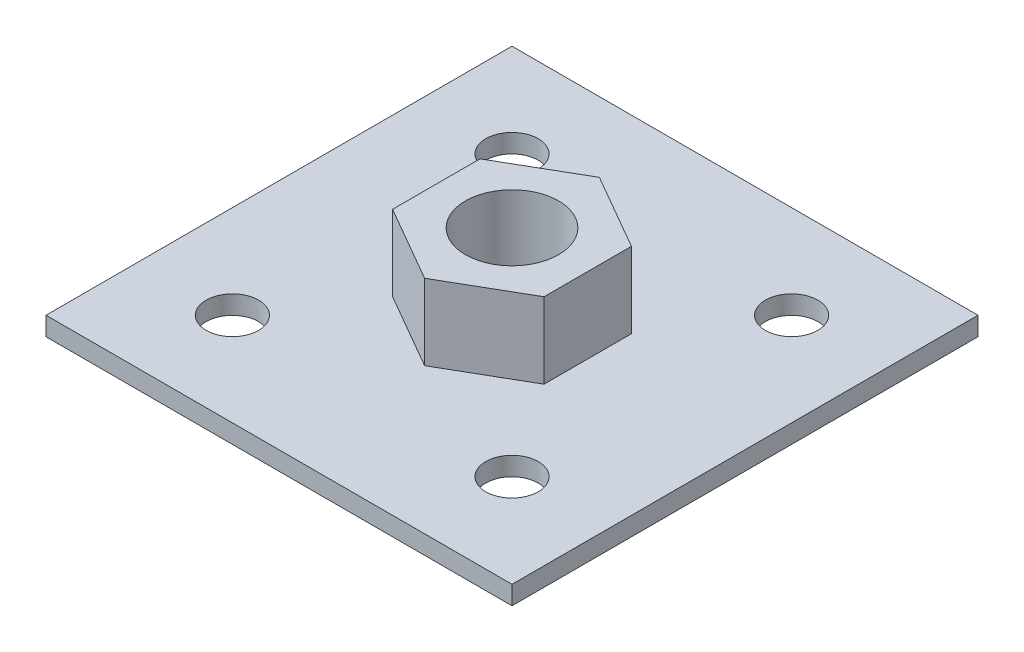
SolidWorks part; units mm, degrees
ref_plane "正面" through (0, 0, 0) normal (0, 0, 1) x (1, 0, 0)
ref_plane "平面" through (0, 0, 0) normal (0, 1, 0) x (1, 0, 0)
ref_plane "右側面" through (0, 0, 0) normal (1, 0, 0) x (0, 0, -1)
sketch "ｽｹｯﾁ1" plane through (0, 0, 0) normal (0, 1, 0) x (1, 0, 0)
  line L1 (-20, -20) -> (20, -20)
  line L2 (-20, -20) -> (-20, 20)
  line L3 (-20, 20) -> (20, 20)
  line L4 (20, -20) -> (20, 20)
  line L5 (-20, -20) -> (20, 20) construction
  line L6 (-20, 20) -> (20, -20) construction
  circle A0 centre (-12, 12) radius 2.25
  circle A1 centre (12, 12) radius 2.25
  circle A2 centre (-12, -12) radius 2.25
  circle A3 centre (12, -12) radius 2.25
  point P0 (0, 0)
  dimension "D4" = 4.5
  dimension "D1" = 40
  dimension "D2" = 40
  dimension "D3" = 24
extrude "ﾎﾞｽ - 押し出し1" add sketch "ｽｹｯﾁ1" along normal blind 1.6
sketch "ｽｹｯﾁ2" plane through (0, 1.6, 0) normal (0, 1, 0) x (1, 0, 0)
  line L0 (0, 7.5) -> (6.5, 3.7517)
  line L1 (6.5, 3.7517) -> (6.5, -3.7517)
  line L2 (6.5, -3.7517) -> (0, -7.5)
  line L3 (0, -7.5) -> (-6.5, -3.7517)
  line L4 (-6.5, -3.7517) -> (-6.5, 3.7517)
  line L5 (-6.5, 3.7517) -> (0, 7.5)
  point P10 (6.5, 0)
  point P11 (-6.5, 0)
  dimension "D1" = 13
  dimension "D2" = 15
extrude "ﾎﾞｽ - 押し出し2" add sketch "ｽｹｯﾁ2" along normal blind 6.5
sketch "ｽｹｯﾁ3" plane through (0, 8.1, 0) normal (0, 1, 0) x (1, 0, 0)
  circle A0 centre (0, 0) radius 4
  dimension "D1" = 8
extrude "ｶｯﾄ - 押し出し1" cut sketch "ｽｹｯﾁ3" against normal through all
